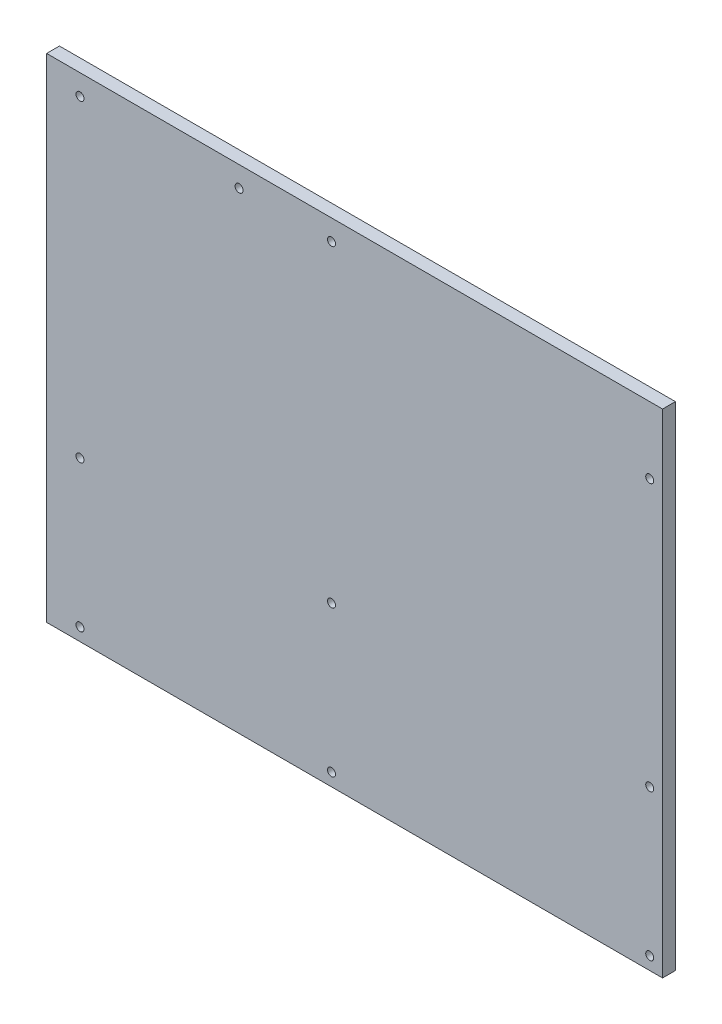
SolidWorks part; units mm, degrees
ref_plane "Front Plane" through (0, 0, 0) normal (0, 0, 1) x (1, 0, 0)
ref_plane "Top Plane" through (0, 0, 0) normal (0, 1, 0) x (1, 0, 0)
ref_plane "Right Plane" through (0, 0, 0) normal (1, 0, 0) x (0, 0, -1)
sketch "Sketch2" plane through (0, 0, 0) normal (0, 0, 1) x (1, 0, 0)
  line L0 (-135.89, -43.18) -> (146.05, -43.18) construction
  line L1 (-152.4, -121.92) -> (152.4, -121.92)
  line L2 (-152.4, -121.92) -> (-152.4, 121.92)
  line L3 (-152.4, 121.92) -> (152.4, 121.92)
  line L4 (152.4, -121.92) -> (152.4, 121.92)
  line L5 (-152.4, -121.92) -> (152.4, 121.92) construction
  line L6 (-152.4, 121.92) -> (152.4, -121.92) construction
  line L7 (-135.89, 111.76) -> (146.05, 111.76) construction
  line L8 (-135.89, 111.76) -> (-135.89, -115.57) construction
  line L9 (-135.89, -115.57) -> (146.05, -115.57) construction
  line L10 (146.05, 111.76) -> (146.05, -115.57) construction
  line L11 (-57.15, 111.76) -> (-57.15, -115.57) construction
  line L12 (-11.43, 111.76) -> (-11.43, -115.57) construction
  line L13 (-3.81, 111.76) -> (-3.81, -115.57) construction
  line L14 (-135.89, 99.06) -> (146.05, 99.06) construction
  point P0 (0, 0)
  dimension "D1" = 304.8
  dimension "D2" = 243.84
  dimension "D3" = 6.35
  dimension "D4" = 10.16
  dimension "D5" = 281.94
  dimension "D6" = 227.33
  dimension "D7" = 154.94
  dimension "D8" = 78.74
  dimension "D9" = 45.72
  dimension "D10" = 7.62
  dimension "D11" = 22.86
extrude "Boss-Extrude1" add sketch "Sketch2" along normal blind 6.35 contours L2 L3 L4 L1
sketch "Sketch3" plane through (0, 0, 6.35) normal (0, 0, 1) x (1, 0, 0)
  line L0 (-135.89, -43.18) -> (146.05, -43.18) construction
  line L1 (-11.43, 111.76) -> (-11.43, -115.57) construction
  line L3 (-152.4, 121.92) -> (152.4, 121.92) construction
  circle A0 centre (-135.89, -43.18) radius 1.9799
  circle A1 centre (-11.43, -43.18) radius 1.9799
  circle A2 centre (146.05, -43.18) radius 1.9799
  circle A3 centre (-135.89, -115.57) radius 1.9799
  circle A4 centre (-11.43, -115.57) radius 1.9799
  circle A5 centre (146.05, -115.57) radius 1.9799
  circle A6 centre (-135.89, 111.76) radius 1.9799
  circle A7 centre (-57.15, 111.76) radius 1.9799
  circle A8 centre (-11.43, 111.76) radius 1.9799
  circle A9 centre (146.05, 88.9) radius 1.9799
  dimension "D1" = 3.9599
  dimension "D2" = 33.02
extrude "Cut-Extrude1" cut sketch "Sketch3" against normal through all
